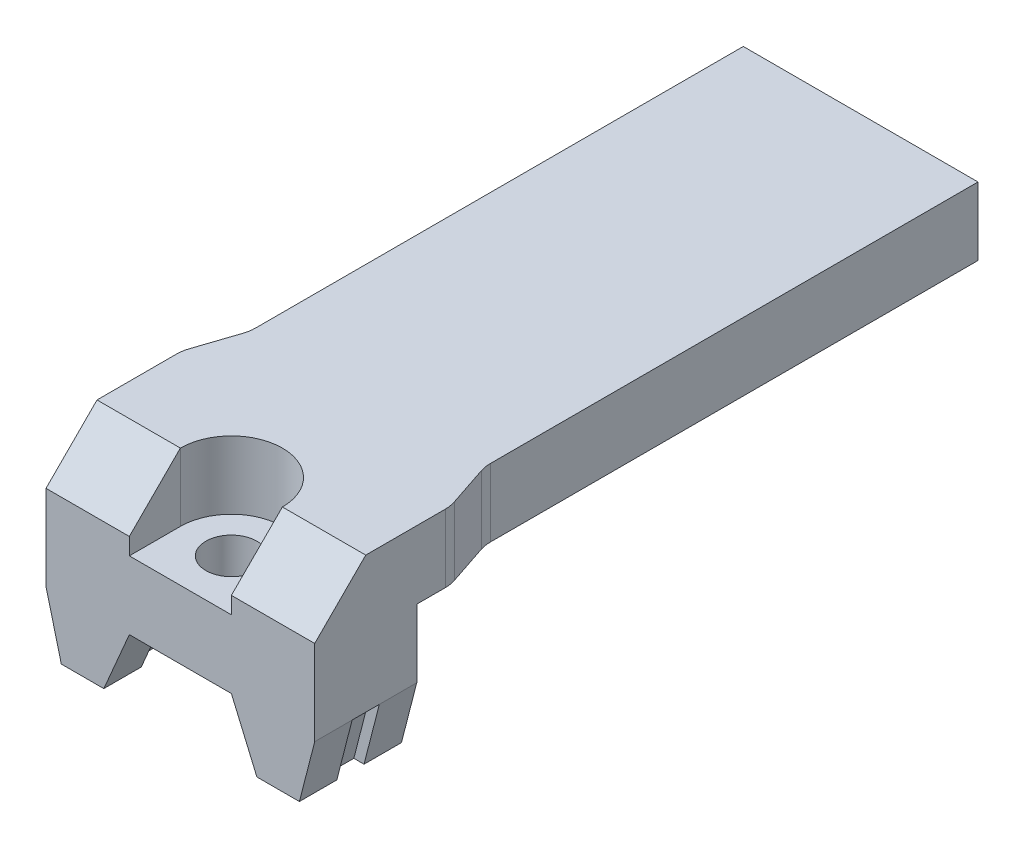
SolidWorks part; units mm, degrees
material "ABS"
ref_plane "正面" through (0, 0, 0) normal (0, 0, 1) x (1, 0, 0)
ref_plane "平面" through (0, 0, 0) normal (0, 1, 0) x (1, 0, 0)
ref_plane "右側面" through (0, 0, 0) normal (1, 0, 0) x (0, 0, -1)
sketch "ｽｹｯﾁ1" plane through (0, 0, 0) normal (0, 1, 0) x (1, 0, 0)
  line L2 (-7.9, 0) -> (-7.9, -48)
  line L3 (-7.9, -48) -> (7.9, -48)
  line L4 (7.9, 0) -> (7.9, -48)
  line L5 (-7.9, 0) -> (7.9, -48) construction
  line L6 (-7.9, -48) -> (7.9, 0) construction
  arc A0 (7.9, 0) -> (-7.9, 0) centre (0, 0) ccw
  point P7 (0, -24)
  dimension "D4" = 48
  dimension "D3" = 15.8
extrude "ﾎﾞｽ - 押し出し1" add sketch "ｽｹｯﾁ1" along normal blind 4
sketch "ｽｹｯﾁ4" plane through (0, 0, 48) normal (0, 0, 1) x (1, 0, 0)
  line L1 (-7, -7.5) -> (-4.5, -7.5)
  line L2 (-4.5, -7.5) -> (-3, -4)
  line L3 (-3, -4) -> (3, -4)
  line L4 (3, -4) -> (4.5, -7.5)
  line L5 (4.5, -7.5) -> (7, -7.5)
  line L7 (7.9, 0) -> (-7.9, 0)
  line L8 (-7, -7.5) -> (-7.9, -4)
  line L9 (-7.9, -4) -> (-7.9, 0)
  line L10 (7.9, 0) -> (7.9, -4)
  line L11 (7.9, -4) -> (7, -7.5)
  dimension "D1" = 7.5
  dimension "D2" = 3.5
  dimension "D3" = 3
  dimension "D4" = 7
  dimension "D5" = 2.5
  dimension "D9" = 4
  dimension "D10" = 4
extrude "ﾎﾞｽ - 押し出し3" add sketch "ｽｹｯﾁ4" against normal blind 6
chamfer "面取り1" distance 3 angle 45 1 edges at (0, 4, 48)
sketch "ｽｹｯﾁ6" plane through (0, 4, 0) normal (0, 1, 0) x (1, 0, 0)
  line L0 (-3, -45) -> (-3, -49)
  line L1 (-3, -49) -> (3, -49)
  line L2 (3, -49) -> (3, -45)
  line L3 (7.9, -48) -> (-7.9, -48) construction
  arc A0 (3, -45) -> (-3, -45) centre (0, -45) ccw
  dimension "D1" = 6
  dimension "D3" = 3
  dimension "D2" = 0
  dimension "D4" = 4
extrude "ｶｯﾄ - 押し出し2" cut sketch "ｽｹｯﾁ6" against normal blind 3.99
sketch "ｽｹｯﾁ7" plane through (0, 0.01, 0) normal (0, 1, 0) x (1, 0, 0)
  circle A0 centre (0, -45) radius 1.5
  dimension "D1" = 3
extrude "ｶｯﾄ - 押し出し3" cut sketch "ｽｹｯﾁ7" against normal up to next
sketch "ｽｹｯﾁ8" plane through (0, 0, 0) normal (0, -1, 0) x (1, 0, 0)
  circle A0 centre (0, 0) radius 6
  dimension "D1" = 12
extrude "ﾎﾞｽ - 押し出し4" add sketch "ｽｹｯﾁ8" along normal blind 1
fillet "ﾌｨﾚｯﾄ1" radius 0.5 1 edges at (0, 0, 6)
sketch "ｽｹｯﾁ9" plane through (0, 4, 0) normal (0, 1, 0) x (1, 0, 0)
  circle A0 centre (0, 0) radius 5
  dimension "D1" = 10
extrude "ｶｯﾄ - 押し出し4" cut sketch "ｽｹｯﾁ9" against normal blind 3
sketch "ｽｹｯﾁ10" plane through (0, 1, 0) normal (0, 1, 0) x (1, 0, 0)
  circle A0 centre (0, 0) radius 3.55
  dimension "D1" = 7.1
extrude "ｶｯﾄ - 押し出し5" cut sketch "ｽｹｯﾁ10" against normal blind 3.6
ref_plane "平面1" through (0, 0, 45) normal (0, 0, 1) x (1, 0, 0)
sketch "ｽｹｯﾁ11" plane through (0, 0, 45) normal (0, 0, 1) x (1, 0, 0)
  line L0 (3, -4) -> (4.5, -7.5)
  line L1 (3, -4) -> (3.6, -4)
  line L2 (4.5, -7.5) -> (5.1, -7.5)
  line L3 (3.6, -4) -> (5.1, -7.5)
  line L4 (3, -4) -> (5.1, -7.5) construction
  line L5 (4.5, -7.5) -> (3.6, -4) construction
  line L6 (-3, -4) -> (3, -4) construction
  line L7 (4.5, -7.5) -> (7, -7.5) construction
  line L8 (6.4, -7.5) -> (7, -7.5)
  line L9 (6.4, -7.5) -> (7.3, -4)
  line L10 (7, -7.5) -> (7.9, -4)
  line L11 (7.3, -4) -> (7.9, -4)
  line L12 (6.4, -7.5) -> (7.9, -4) construction
  line L13 (7, -7.5) -> (7.3, -4) construction
  point P5 (4.05, -5.75)
  point P18 (7.15, -5.75)
  dimension "D1" = 0.6
extrude "ｶｯﾄ - 押し出し6" cut sketch "ｽｹｯﾁ11" against normal mid plane 1.6
mirror "ﾐﾗｰ1" about plane through (0, 0, 0) normal (1, 0, 0) of "ｶｯﾄ - 押し出し6"
sketch "ｽｹｯﾁ12" plane through (0, 4, 0) normal (0, 1, 0) x (1, 0, 0)
  line L0 (-7.9, 0) -> (-7.9, -40)
  line L1 (-7.9, 0) -> (-7.9, -45) construction
  line L2 (-7.9, -40) -> (-6.9, -37)
  line L3 (-6.9, -37) -> (-6.9, -3.8471)
  line L4 (7.9, -48) -> (3, -48) construction
  arc A0 (-7.9, 0) -> (-6.9, -3.8471) centre (0, 0) ccw
  arc A1 (7.9, 0) -> (-7.9, 0) centre (0, 0) ccw construction
  dimension "D1" = 6.9
  dimension "D2" = 3
  dimension "D3" = 11
extrude "ｶｯﾄ - 押し出し7" cut sketch "ｽｹｯﾁ12" against normal through all
mirror "ﾐﾗｰ2" about plane through (0, 0, 0) normal (1, 0, 0) of "ｶｯﾄ - 押し出し7"
fillet "ﾌｨﾚｯﾄ2" radius 2 6 edges at (6.9, 2, 3.8471) (7.9, 2, 40) (6.9, 2, 37) (-7.9, 2, 40) (-6.9, 2, 37) (-6.9, 2, 3.8471)
ref_plane "平面2" through (0, 0, 8) normal (0, 0, 1) x (1, 0, 0)
other "ｻｰﾌｪｽ ｶｯﾄ1"
